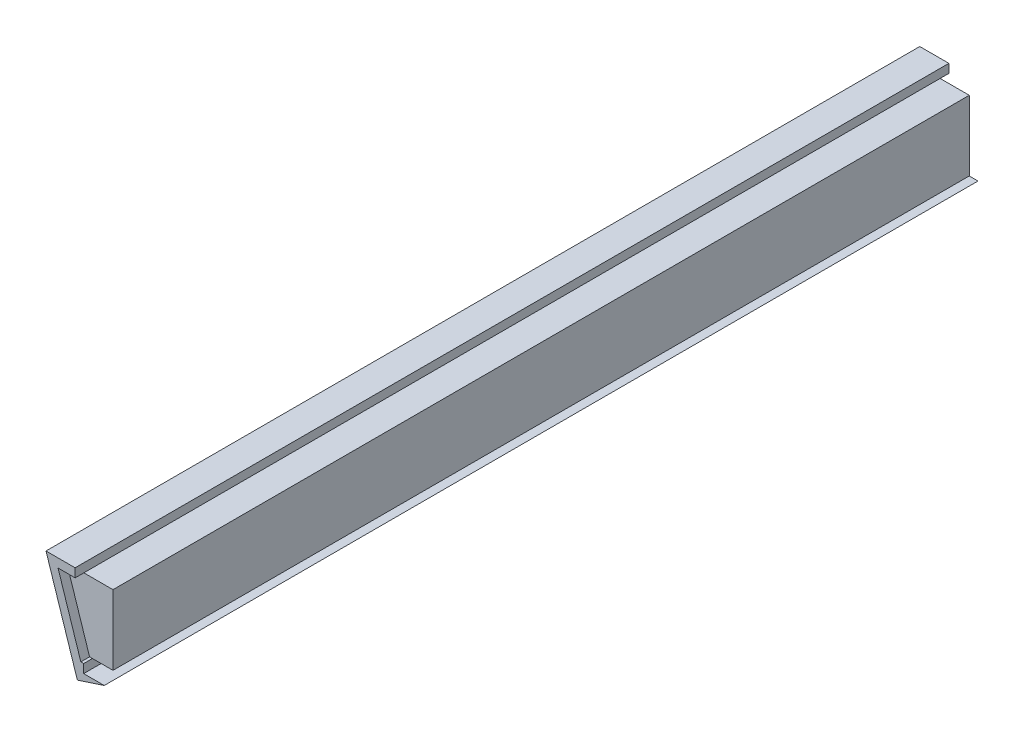
SolidWorks part; units mm, degrees
ref_plane "Front Plane" through (0, 0, 0) normal (0, 0, 1) x (1, 0, 0)
ref_plane "Top Plane" through (0, 0, 0) normal (0, 1, 0) x (1, 0, 0)
ref_plane "Right Plane" through (0, 0, 0) normal (1, 0, 0) x (0, 0, -1)
sketch "Sketch1" plane through (0, 0, 0) normal (0, 0, 1) x (1, 0, 0)
  line L0 (1.4223, -33.2385) -> (-138.087, 394.5899)
  line L1 (-8.2, 296) -> (-105.9381, 296)
  line L2 (-105.9381, 296) -> (-95.9381, 296)
  line L3 (-95.9381, 296) -> (-95.9381, 293)
  line L4 (-95.9381, 293) -> (-85.9381, 293)
  line L5 (-85.9381, 293) -> (-85.9381, 269)
  line L6 (-93, 269) -> (0, 269) construction
  line L7 (-85.9381, 269) -> (-93, 269)
  line L8 (-93, 269) -> (-93, 266)
  line L9 (-93, 266) -> (-85.9381, 266)
  line L10 (-93, 266) -> (0, 266) construction
  line L11 (-85.9381, 266) -> (-95.1734, 262.9885)
extrude "Boss-Extrude1" add sketch "Sketch1" against normal blind 300 contours L11 L9 L8 L7 L5 L4 L3 L1 L0
sketch "Sketch2" plane through (0, 0, -300) normal (0, 0, -1) x (-1, 0, 0)
  line L0 (93, 266) -> (102.7826, 296)
  line L1 (95.9381, 296) -> (105.9381, 296) construction
  line L2 (95.9381, 293) -> (101.8043, 293)
  line L3 (95.9381, 293) -> (85.9381, 293)
  line L4 (85.9381, 293) -> (85.9381, 269)
  line L5 (85.9381, 269) -> (93.9783, 269)
  line M5 (95.9381, 293) -> (85.9381, 293)
  line M6 (85.9381, 293) -> (85.9381, 269)
  line M7 (85.9381, 269) -> (93, 269)
extrude "Cut-Extrude1" cut sketch "Sketch2" against normal blind 3 contours L5 L0 L2 M7 M5 M6
sketch "Sketch3" plane through (0, 0, 0) normal (0, 0, 1) x (1, 0, 0)
  line L0 (-93, 266) -> (-102.7826, 296)
  line L1 (-95.9381, 296) -> (-105.9381, 296) construction
  line L2 (-85.9381, 293) -> (-101.8043, 293)
  line L3 (-85.9381, 293) -> (-85.9381, 269)
  line L4 (-85.9381, 269) -> (-93.9783, 269)
  line M4 (-93, 269) -> (-85.9381, 269)
  line M5 (-85.9381, 269) -> (-85.9381, 293)
  line M6 (-85.9381, 293) -> (-95.9381, 293)
extrude "Cut-Extrude2" cut sketch "Sketch3" against normal blind 3 contours L4 L2 L0 M4 M5 M6
